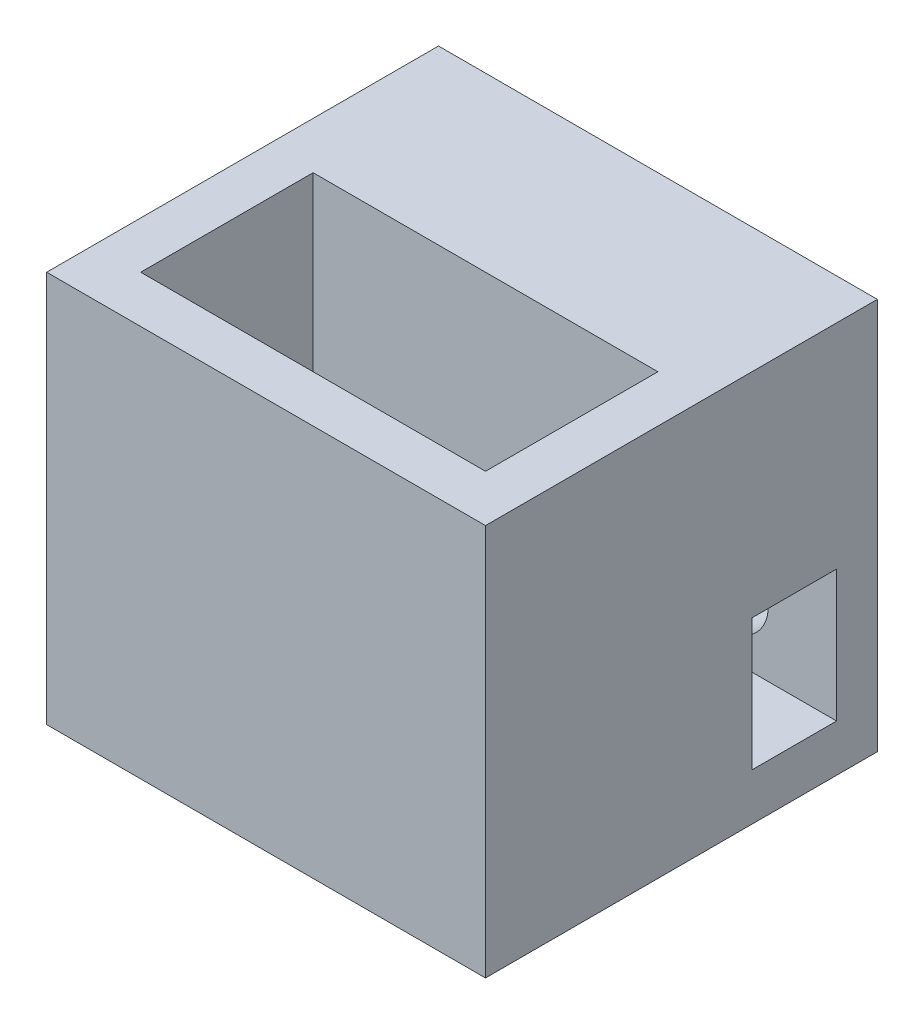
SolidWorks part; units mm, degrees
material "ABS"
ref_plane "Front Plane" through (0, 0, 0) normal (0, 0, 1) x (1, 0, 0)
ref_plane "Top Plane" through (0, 0, 0) normal (0, 1, 0) x (1, 0, 0)
ref_plane "Right Plane" through (0, 0, 0) normal (1, 0, 0) x (0, 0, -1)
sketch "Sketch1" plane through (0, 0, 0) normal (0, 1, 0) x (1, 0, 0)
  line L0 (0, 0) -> (11, 0) construction
  line L1 (-11, -5.5) -> (11, -5.5)
  line L2 (-11, -5.5) -> (-11, 5.5)
  line L3 (-11, 5.5) -> (11, 5.5)
  line L4 (11, -5.5) -> (11, 5.5)
  line L5 (-11, -5.5) -> (11, 5.5) construction
  line L6 (-11, 5.5) -> (11, -5.5) construction
  line L11 (-14, 8.5) -> (0, 8.5)
  line L17 (14, -8.5) -> (14, 8.5)
  line L18 (-14, -8.5) -> (0, -8.5)
  line L23 (-14, -8.5) -> (-14, 8.5)
  line L29 (0, 0) -> (0, 5.5) construction
  line L34 (0, 8.5) -> (14, 8.5)
  line L35 (0, -8.5) -> (14, -8.5)
  line L36 (-14, 8.5) -> (14, 8.5) construction
  line L38 (-14, -8.5) -> (14, -8.5) construction
  point P0 (0, 0)
  point P6 (0, 0)
  point P12 (11.3271, 7.5)
  point P13 (0, 7.5)
  dimension "D1" = 11
  dimension "D2" = 22
  dimension "D3" = 3
extrude "Boss-Extrude1" add sketch "Sketch1" along normal blind 23
sketch "Sketch2" plane through (0, 0, 0) normal (0, -1, 0) x (1, 0, 0)
  line L0 (0, 0) -> (0, 8.5) construction
  line L1 (-14, 8.5) -> (14, 8.5) construction
  line L22 (-14, 8.5) -> (-14, -8.5)
  line L23 (-14, -8.5) -> (14, -8.5)
  line L28 (14, -8.5) -> (14, 8.5)
  line L29 (14, 8.5) -> (-14, 8.5)
  line L34 (-14, 8.5) -> (-14, -8.5)
  line L35 (-14, -8.5) -> (14, -8.5)
  line L40 (14, -8.5) -> (14, 8.5)
  line L41 (14, 8.5) -> (-14, 8.5)
  circle A0 centre (-5.5, 0) radius 3
  circle A1 centre (5.5, 0) radius 3
  dimension "D2" = 6
  dimension "D1" = 11
  dimension "D3" = 0
extrude "Boss-Extrude2" add sketch "Sketch2" along normal blind 2
sketch "Sketch10" plane through (14, 0, 0) normal (1, 0, 0) x (0, 0, -1)
  line L0 (8.5, -2) -> (-8.5, -2) construction
  line L1 (8.5, 23) -> (16.5, 23)
  line L2 (8.5, 23) -> (8.5, -2)
  line L3 (8.5, -2) -> (16.5, -2)
  line L4 (16.5, 23) -> (16.5, -2)
  line L5 (8.5, 9.4) -> (13.9, 9.4)
  line L6 (13.9, 9.4) -> (13.9, 1)
  line L7 (13.9, 1) -> (8.5, 1)
  line M9 (8.5, -2) -> (8.5, 23)
  dimension "D1" = 8
  dimension "D2" = 5.4
  dimension "D3" = 3
  dimension "D4" = 8.4
extrude "Boss-Extrude7" add sketch "Sketch10" against normal through all contours L6 L7 L3 L4 L1 L2 L5 M9
sketch "Sketch11" plane through (0, 0, -13.9) normal (0, 0, 1) x (1, 0, 0)
  line L0 (-14, 5.2) -> (14, 5.2) construction
  line L1 (-14, 9.4) -> (-14, 1) construction
  line L2 (14, 9.4) -> (14, 1) construction
  line L3 (0, 5.2) -> (0, 8.2) construction
  line L4 (4.5751, 1) -> (2.1503, 5.2)
  line L5 (-2.1503, 5.2) -> (-4.5751, 9.4)
  line L6 (-4.5751, 9.4) -> (-9.4249, 9.4) construction
  line L7 (-9.4249, 9.4) -> (-11.8497, 5.2) construction
  line L8 (-11.8497, 5.2) -> (-9.4249, 1) construction
  line L9 (-9.4249, 1) -> (-4.5751, 1) construction
  line L10 (-4.5751, 1) -> (-2.1503, 5.2)
  line L11 (9.4249, 1) -> (4.5751, 1) construction
  line L12 (11.8497, 5.2) -> (9.4249, 1) construction
  line L13 (9.4249, 9.4) -> (11.8497, 5.2) construction
  line L14 (4.5751, 9.4) -> (9.4249, 9.4) construction
  line L15 (2.1503, 5.2) -> (4.5751, 9.4)
  line L16 (-4.5751, 9.4) -> (4.5751, 9.4)
  line L17 (-4.5751, 1) -> (4.5751, 1)
  circle A0 centre (-7, 5.2) radius 4.2 construction
  point P9 (7, 5.2)
  point P10 (-7, 5.2)
  dimension "D1" = 3
  dimension "D2" = 14
  dimension "D3" = 8.4
extrude "Boss-Extrude8" add sketch "Sketch11" along normal up to next
hole_wizard "M5 Clearance Hole2" positions "Sketch12" profile "Sketch13" hole size "M5" standard "ANSI Metric"
sketch "Sketch12" plane through (0, 0, -13.9) normal (0, 0, 1) x (1, 0, 0)
  point P0 (-7, 5.2)
  point P3 (7, 5.2)
sketch "Sketch13" plane through (-7, 5.2, -13.9) normal (1, 0, 0) x (0, -1, 0)
  line L0 (0, 0) -> (0, 2.6)
  line L1 (0, 2.6) -> (2.65, 2.6)
  line L2 (2.65, 2.6) -> (2.65, 0)
  line L5 (2.65, 0) -> (0, 0)
  line L11 (0, -6.35) -> (0, 107.95) construction
  dimension "Thru Hole Dia." = 5.3
  dimension "Thru Hole Depth" = 2.6
